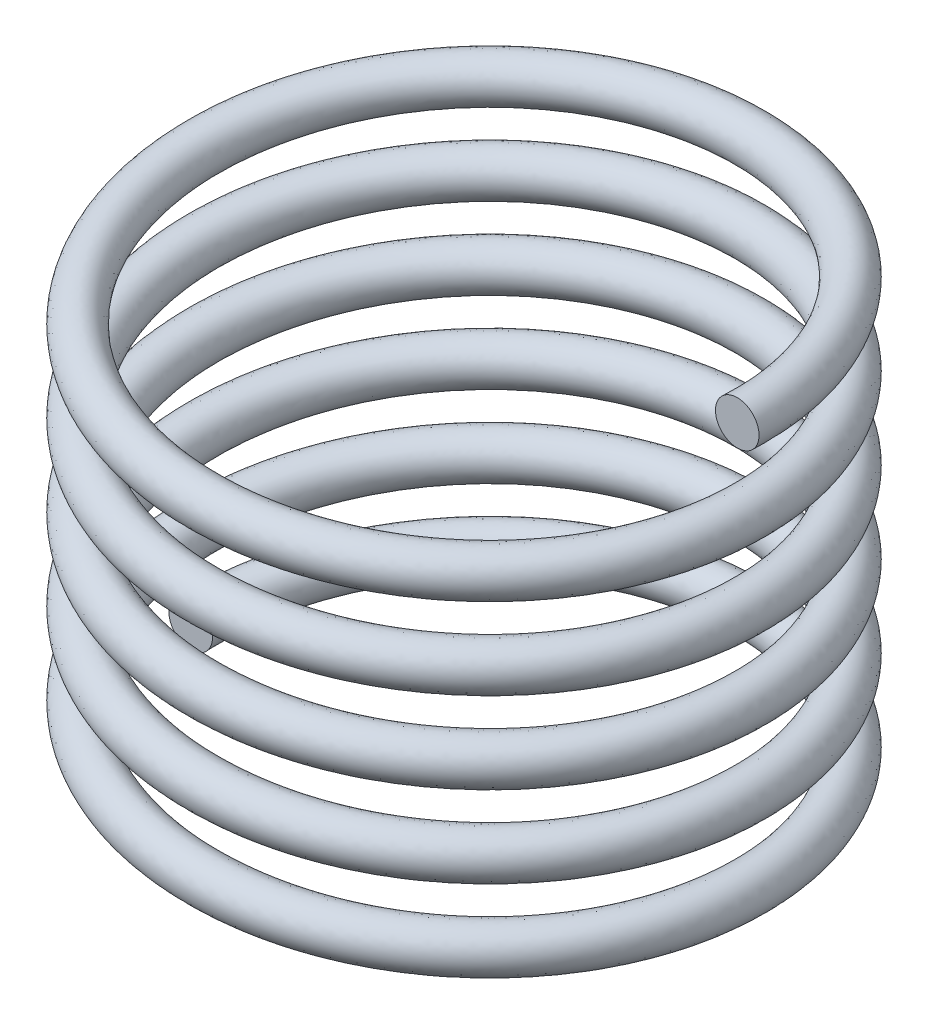
SolidWorks part; units mm, degrees
material "Alloy Steel"
ref_plane "Front Plane" through (0, 0, 0) normal (0, 0, 1) x (1, 0, 0)
ref_plane "Top Plane" through (0, 0, 0) normal (0, 1, 0) x (1, 0, 0)
ref_plane "Right Plane" through (0, 0, 0) normal (1, 0, 0) x (0, 0, -1)
sketch "Sketch1" plane through (0, 0, 0) normal (0, 0, 1) x (1, 0, 0)
  circle A0 centre (-14.3256, 0) radius 1.143
  dimension "D1" = 14.3256
  dimension "D2" = 2.286
sketch "Sketch2" plane through (0, 0, 0) normal (0, 1, 0) x (1, 0, 0)
  circle A0 centre (0, 0) radius 14.3256
curve "Helix/Spiral1" pitch 4.2718 height 23.495 turns 5.5
sweep "Sweep1" add profiles "Sketch1" path "Helix/Spiral1"
